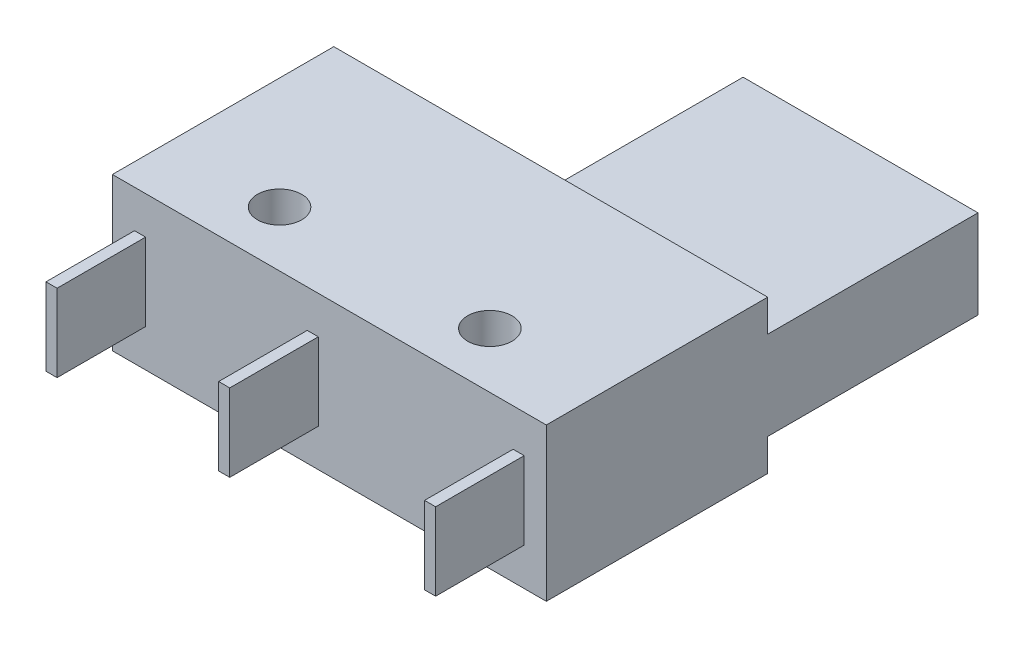
SolidWorks part; units mm, degrees
ref_plane "Front Plane" through (0, 0, 0) normal (0, 0, 1) x (1, 0, 0)
ref_plane "Top Plane" through (0, 0, 0) normal (0, 1, 0) x (1, 0, 0)
ref_plane "Right Plane" through (0, 0, 0) normal (1, 0, 0) x (0, 0, -1)
sketch "Sketch1" plane through (0, 0, 0) normal (0, 1, 0) x (1, 0, 0)
  line L1 (0, 0) -> (19.6, 0)
  line L2 (0, 0) -> (0, 10)
  line L3 (0, 10) -> (19.6, 10)
  line L4 (19.6, 0) -> (19.6, 10)
  dimension "D1" = 19.6
  dimension "D2" = 10
extrude "Boss-Extrude1" add sketch "Sketch1" along normal blind 6.9
sketch "Sketch2" plane through (0, 0, 0) normal (0, 0, 1) x (1, 0, 0)
  line L0 (1, 5.2) -> (0, 5.2) construction
  line L1 (1, 5.2) -> (1.5, 5.2)
  line L2 (1, 5.2) -> (1, 1.7)
  line L3 (1, 1.7) -> (1.5, 1.7)
  line L4 (1.5, 5.2) -> (1.5, 1.7)
  line L5 (8.8, 5.2) -> (9.3, 5.2)
  line L6 (8.8, 5.2) -> (8.8, 1.7)
  line L7 (8.8, 1.7) -> (9.3, 1.7)
  line L8 (9.3, 5.2) -> (9.3, 1.7)
  line L9 (18.1, 5.2) -> (18.6, 5.2)
  line L10 (18.1, 5.2) -> (18.1, 1.7)
  line L11 (18.1, 1.7) -> (18.6, 1.7)
  line L12 (18.6, 5.2) -> (18.6, 1.7)
  line L13 (0, 6.9) -> (0, 0) construction
  line L14 (18.6, 5.2) -> (19.6, 5.2) construction
  line L15 (19.6, 6.9) -> (19.6, 0) construction
  line L16 (1, 5.2) -> (1, 6.9) construction
  line L17 (0, 6.9) -> (19.6, 6.9) construction
  line L18 (1, 1.7) -> (1, 0) construction
  line L19 (0, 0) -> (19.6, 0) construction
  dimension "D1" = 0.5
  dimension "D2" = 7.3
  dimension "D3" = 8.8
  dimension "D4" = 3.5
extrude "Boss-Extrude2" add sketch "Sketch2" along normal blind 4
sketch "Sketch3" plane through (0, 0, -10) normal (0, 0, -1) x (-1, 0, 0)
  line L0 (-19.6, 6.9) -> (-19.6, 0) construction
  line L1 (-19.6, 5.45) -> (-8.9888, 5.45)
  line L2 (-19.6, 5.45) -> (-19.6, 1.45)
  line L3 (-19.6, 1.45) -> (-8.9888, 1.45)
  line L4 (-8.9888, 5.45) -> (-8.9888, 1.45)
  line L5 (-8.9888, 5.45) -> (-8.9888, 6.9) construction
  line L6 (-19.6, 6.9) -> (0, 6.9) construction
  line L7 (-8.9888, 1.45) -> (-8.9888, 0) construction
  line L8 (-19.6, 0) -> (0, 0) construction
  dimension "D1" = 4
extrude "Boss-Extrude3" add sketch "Sketch3" along normal blind 9.5
sketch "Sketch5" plane through (0, 6.9, 0) normal (0, 1, 0) x (1, 0, 0)
  line L0 (0, 0) -> (19.6, 0) construction
  line L1 (5.05, 2.5) -> (0, 2.5) construction
  line L2 (0, 10) -> (0, 0) construction
  line L3 (14.55, 2.5) -> (19.6, 2.5) construction
  line L4 (19.6, 0) -> (19.6, 10) construction
  circle A0 centre (5.05, 2.5) radius 1
  circle A1 centre (14.55, 2.5) radius 1
  dimension "D1" = 2
  dimension "D2" = 2
  dimension "D3" = 9.5
  dimension "D4" = 2.5
extrude "Cut-Extrude1" cut sketch "Sketch5" against normal through all
